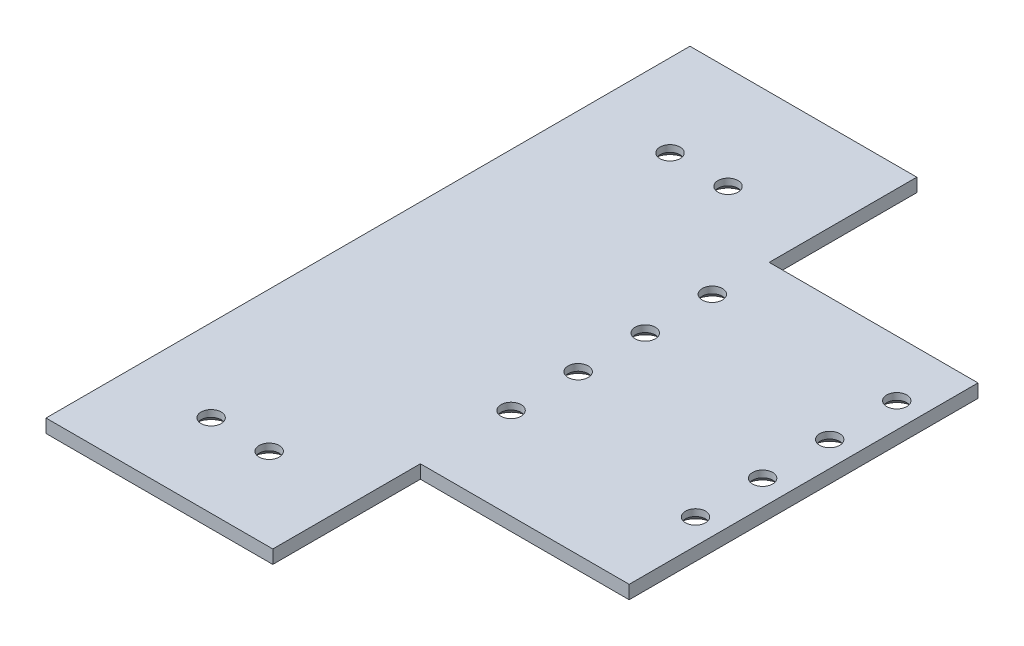
SolidWorks part; units mm, degrees
ref_plane "Спереди" through (0, 0, 0) normal (0, 0, 1) x (1, 0, 0)
ref_plane "Сверху" through (0, 0, 0) normal (0, 1, 0) x (1, 0, 0)
ref_plane "Справа" through (0, 0, 0) normal (1, 0, 0) x (0, 0, -1)
sketch "Эскиз1" plane through (0, 0, 0) normal (0, 1, 0) x (1, 0, 0)
  line L5 (49.9338, 26) -> (18.8099, 26)
  line L6 (49.9338, 26) -> (49.9338, -26)
  line L7 (49.9338, -26) -> (18.8099, -26)
  line L8 (-48.9591, 48) -> (15, 48)
  line L9 (-48.9591, 48) -> (-48.9591, -48)
  line L10 (-50, 0) -> (49.9338, 0) construction
  line L11 (-48.9591, -48) -> (15, -48)
  line L12 (-45.2656, -36.9305) -> (-45.2656, -25.3095)
  line L13 (-45.2656, 36.9305) -> (-27.3726, 36.9305)
  line L14 (-45.2656, 36.9305) -> (-45.2656, 25.3095)
  line L15 (-45.2656, 25.3095) -> (-27.3726, 25.3095)
  line L16 (-27.3726, 36.9305) -> (-27.3726, 25.3095)
  line L21 (-45.2656, -25.3095) -> (-27.3726, -25.3095)
  line L22 (-27.3726, -36.9305) -> (-27.3726, -25.3095)
  line L23 (-45.2656, -36.9305) -> (-27.3726, -36.9305)
  line L24 (-15.0662, -48) -> (20.6445, -48) construction
  line L27 (15, -48) -> (18.8099, -48)
  line L28 (18.8099, -26) -> (18.8099, -48)
  line L29 (15, 48) -> (18.8099, 48)
  line L30 (18.8099, 26) -> (18.8099, 48)
  line L31 (19.8099, 48) -> (19.8099, 26) construction
  line L32 (18.0113, 27.0025) -> (47.8563, 27.0025) construction
  dimension "D1" = 1
  dimension "D2" = 1.0025
extrude "Бобышка-Вытянуть1" add sketch "Эскиз1" along normal blind 2
sketch "Эскиз2" plane through (0, 2, 0) normal (0, 1, 0) x (1, 0, 0)
  circle A0 centre (46.1838, -12.3573) radius 1.5
  circle A1 centre (18.6838, -12.3573) radius 1.5
  circle A2 centre (18.6838, -2.3573) radius 1.5
  circle A3 centre (46.1838, -2.3573) radius 1.5
  circle A4 centre (18.6838, 7.6427) radius 1.5
  circle A5 centre (46.1838, 7.6427) radius 1.5
  circle A6 centre (18.6838, 17.6427) radius 1.5
  circle A7 centre (46.1838, 17.6427) radius 1.5
  dimension "D1" = 4
extrude "Вырез-Вытянуть1" cut sketch "Эскиз2" against normal blind 10
chamfer "Фаска1" distance 1 angle 45 8 edges at (18.6838, 0, -19.1427) (18.6838, 0, -9.1427) (18.6838, 0, 0.8573) (18.6838, 0, 10.8573) (46.1838, 0, -19.1427) (46.1838, 0, -9.1427) (46.1838, 0, 0.8573) (46.1838, 0, 10.8573)
sketch "Эскиз3" plane through (0, 2, 0) normal (0, 1, 0) x (1, 0, 0)
  circle A0 centre (5.9236, 32.747) radius 1.5
  circle A1 centre (-2.7264, 32.747) radius 1.5
  circle A2 centre (-2.7264, -35.6602) radius 1.5
  circle A3 centre (5.9236, -35.6602) radius 1.5
extrude "Вырез-Вытянуть2" cut sketch "Эскиз3" against normal blind 10
sketch "Эскиз4" plane through (0, 2, 0) normal (0, 1, 0) x (1, 0, 0)
  line L0 (49.9338, 26) -> (49.9338, -48) construction
  line L1 (-48.9591, -48) -> (15, -48) construction
  line L2 (15, -48) -> (49.9338, -48) construction
  line L3 (18.8099, 48) -> (-48.9591, 48) construction
  line L9 (-48.9591, 48) -> (-15.0021, 48)
  line L10 (-48.9591, 48) -> (-48.9591, -48)
  line L11 (-48.9591, -48) -> (-15.0021, -48)
  line L12 (-15.0021, 48) -> (-15.0021, -48)
extrude "Вырез-Вытянуть3" cut sketch "Эскиз4" against normal blind 10
chamfer "Фаска2" distance 1 angle 45 4 edges at (-2.7264, 0, 34.1602) (5.9236, 0, 34.1602) (-2.7264, 0, -34.247) (5.9236, 0, -34.247)
